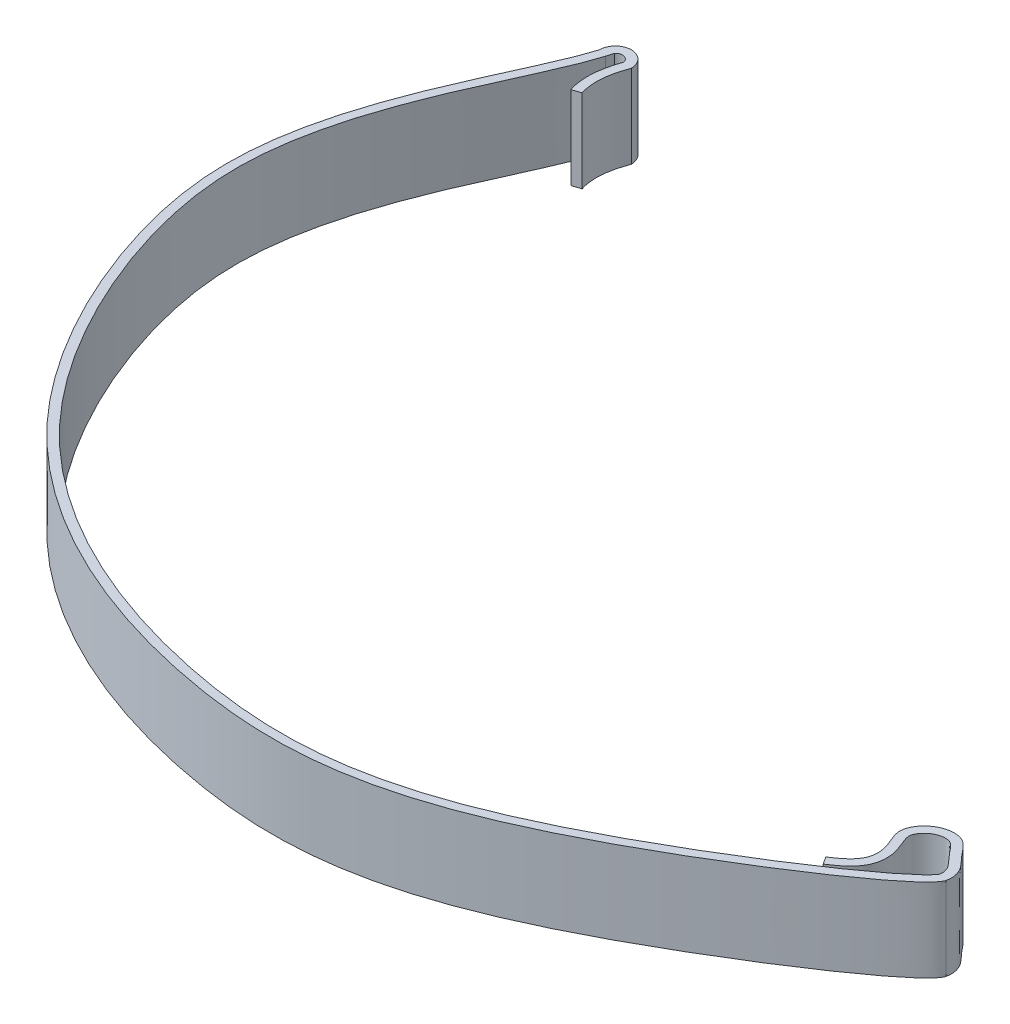
SolidWorks part; units mm, degrees
ref_plane "Front Plane" through (0, 0, 0) normal (0, 0, 1) x (1, 0, 0)
ref_plane "Top Plane" through (0, 0, 0) normal (0, 1, 0) x (1, 0, 0)
ref_plane "Right Plane" through (0, 0, 0) normal (1, 0, 0) x (0, 0, -1)
sketch "Sketch1" plane through (0, 0, 0) normal (0, 1, 0) x (1, 0, 0)
  line L0 (81.9243, 3.8733) -> (82.7355, 2.6116)
  line L1 (-49.99, 94.7614) -> (-51.4137, 94.2891)
  line L2 (-53.374, 102.069) -> (-53.031, 103.262)
  arc A0 (-49.4423, 102.4957) -> (-54.8121, 102.4957) centre (-52.1272, 102.4957) ccw
  arc A1 (-50.9622, 102.7123) -> (-53.031, 103.262) centre (-52.1272, 102.4957) ccw
  arc A2 (-50.9622, 102.7123) -> (-53.3121, 102.4957) centre (-52.1272, 102.4957) ccw construction
  spline S0 degree 3 poles (-54.8121, 102.4957) (-57.6014, 93.0952) (-70.8155, 72.6299) (-68.8012, 37.1217) (-48.9098, -7.4042) (9.5425, -29.9258) (48.2924, -23.113) (94.7327, 7.5617) (95.4576, 10.5593) knots 0 0 0 0 0.23059 0.273328 0.427372 0.626139 0.858258 1 1 1 1
  spline S1 degree 3 poles (-49.4423, 102.4957) (-50.3687, 100.0761) (-50.8248, 97.2778) (-49.99, 94.7614) knots 0 0 0 0 1 1 1 1
  spline S2 degree 3 poles (95.4576, 10.5593) (95.6783, 11.4195) (95.3722, 13.3247) (93.1104, 15.3311) (91.2056, 18.4759) (86.5276, 18.1592) (83.4335, 14.1399) (85.712, 10.7312) (85.8615, 6.555) (83.2549, 4.7288) (81.9243, 3.8733) knots 0 0 0 0 0.091657 0.181035 0.30867 0.439133 0.59716 0.725261 0.823506 1 1 1 1
  spline S3 degree 1 poles (-50.9622, 102.7123) (-51.4137, 94.2891) knots 0 0 1 1 construction
  spline S4 degree 3 poles (-51.4137, 94.2891) (-51.6468, 94.9917) (-51.9478, 96.4713) (-51.9429, 98.6362) (-51.5947, 100.7499) (-51.1975, 102.0627) (-50.9622, 102.7123) knots 0.040295 0.040295 0.040295 0.040295 0.280221 0.520147 0.760074 1 1 1 1
  spline S5 degree 1 poles (-53.374, 102.069) (94.0067, 10.9398) knots 0 0 1 1 construction
  spline S6 degree 1 poles (94.0067, 10.9398) (82.7355, 2.6116) knots 0 0 1 1 construction
  spline S7 degree 3 poles (-53.374, 102.069) (-53.4764, 101.7239) (-53.6908, 101.0503) (-54.1966, 99.6165) (-54.9413, 97.7294) (-55.9875, 95.2915) (-57.5395, 91.8245) (-59.6914, 87.1004) (-62.3436, 80.8883) (-64.7955, 74.2222) (-66.7772, 67.2045) (-68.025, 59.9114) (-68.2714, 52.5214) (-67.3144, 44.6537) (-65.0323, 35.8723) (-61.548, 26.7348) (-56.9668, 17.6553) (-51.4037, 9.0652) (-44.9853, 1.4338) (-37.8116, -4.9858) (-27.4873, -12.1186) (-13.6425, -18.5256) (2.9679, -22.8405) (17.8028, -24.4465) (29.7279, -23.2328) (39.8181, -20.5008) (47.839, -17.5062) (55.0519, -14.1698) (61.2213, -10.969) (67.7006, -7.3956) (74.3546, -3.4435) (80.5322, 0.4827) (84.7668, 3.3141) (87.8273, 5.4936) (89.9099, 7.0748) (91.2664, 8.1642) (92.3932, 9.1395) (93.1176, 9.8384) (93.5501, 10.3082) (93.7955, 10.6073) (93.9269, 10.7959) (93.9891, 10.9033) (93.9998, 10.9246) (94.0067, 10.9398) knots 0 0 0 0 0.007785 0.01557 0.03114 0.04671 0.062279 0.093419 0.124559 0.155698 0.186838 0.217978 0.249117 0.280257 0.311397 0.342536 0.373676 0.404816 0.435955 0.467095 0.498235 0.560514 0.622793 0.685073 0.747352 0.778492 0.809631 0.840771 0.856341 0.871911 0.90305 0.91862 0.93419 0.94976 0.957545 0.96533 0.973115 0.9809 0.984792 0.988685 0.992577 0.994523 0.99647 0.99647 0.99647 0.99647
  spline S8 degree 3 poles (94.0067, 10.9398) (94.0471, 11.101) (94.08, 11.4192) (93.9918, 11.9968) (93.7878, 12.4934) (93.435, 12.9867) (92.8764, 13.5876) (92.1574, 14.3681) (91.544, 15.1579) (91.0096, 15.816) (90.5208, 16.2932) (90.1437, 16.5336) (89.6799, 16.6748) (88.875, 16.7167) (87.7336, 16.4217) (86.737, 15.662) (86.1845, 14.9296) (85.9359, 14.3853) (85.857, 13.9473) (85.9023, 13.5327) (86.1204, 12.8593) (86.4771, 12.03) (86.8784, 11.027) (87.165, 9.8504) (87.2405, 8.65) (87.0819, 7.4184) (86.6101, 6.2244) (85.9382, 5.2426) (85.1575, 4.4121) (84.3305, 3.7107) (83.4914, 3.1037) (82.9951, 2.7786) (82.7355, 2.6116) knots 0.000545 0.000545 0.000545 0.000545 0.031778 0.063011 0.094244 0.125477 0.15671 0.187943 0.219176 0.250409 0.281642 0.312875 0.344108 0.375341 0.437807 0.500273 0.531506 0.562739 0.593972 0.625205 0.656438 0.68767 0.718903 0.750136 0.781369 0.812602 0.843835 0.875068 0.906301 0.937534 0.968767 1 1 1 1
  dimension "D1" = 1.5
extrude "Boss-Extrude1" add sketch "Sketch1" along normal blind 14 contours S8 S7 L2 A1 S4 L1 S1 A0 S0 S2 L0
